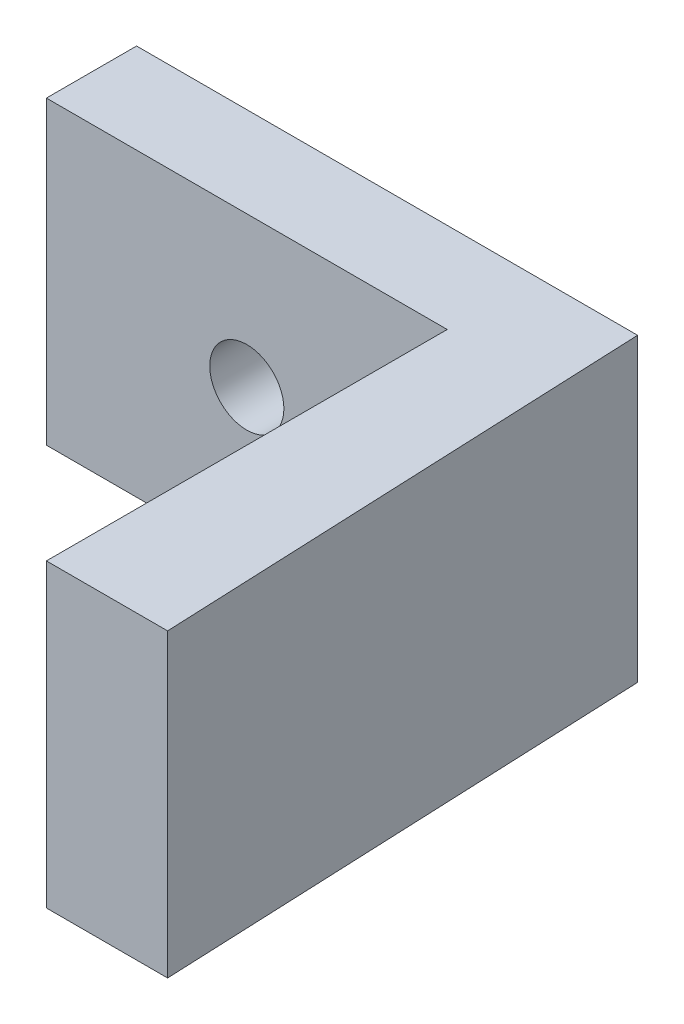
SolidWorks part; units mm, degrees
ref_plane "Front" through (0, 0, 0) normal (0, 0, 1) x (1, 0, 0)
ref_plane "Top" through (0, 0, 0) normal (0, 1, 0) x (1, 0, 0)
ref_plane "Right" through (0, 0, 0) normal (1, 0, 0) x (0, 0, -1)
sketch "Sketch1" plane through (0, 0, 0) normal (0, 1, 0) x (1, 0, 0)
  line L0 (20, 4.5) -> (25, 4.5)
  line L1 (0, 0) -> (20, 0)
  line L2 (0, 0) -> (0, 4.5)
  line L3 (0, 4.5) -> (20, 4.5)
  line L4 (20, 0) -> (20, 4.5) construction
  line L5 (25, 4.5) -> (26.0483, -20)
  line L6 (26.0483, -20) -> (20, -20)
  line L7 (20, -20) -> (20, 0)
  line L8 (25, 4.5) -> (30.5121, 4.5) construction
  dimension "D1" = 20
  dimension "D2" = 4.5
  dimension "D3" = 5
  dimension "D4" = 87.55
  dimension "D5" = 20
extrude "Boss-Extrude1" add sketch "Sketch1" along normal blind 15
sketch "Sketch2" plane through (0, 0, 0) normal (0, 0, 1) x (1, 0, 0)
  line L0 (0, 7.5) -> (20, 7.5) construction
  line L3 (10, 15) -> (10, 0) construction
  line L4 (0, 15) -> (20, 15) construction
  line L5 (0, 0) -> (20, 0) construction
  line L6 (0, 15) -> (0, 0) construction
  line L7 (20, 15) -> (20, 0) construction
  circle A0 centre (10, 7.5) radius 1.85
  circle A1 centre (10, 7.5) radius 3.5 construction
  point P12 (10, 7.5)
  dimension "D1" = 3.7
  dimension "D2" = 7
extrude "Cut-Extrude1" cut sketch "Sketch2" against normal through all
